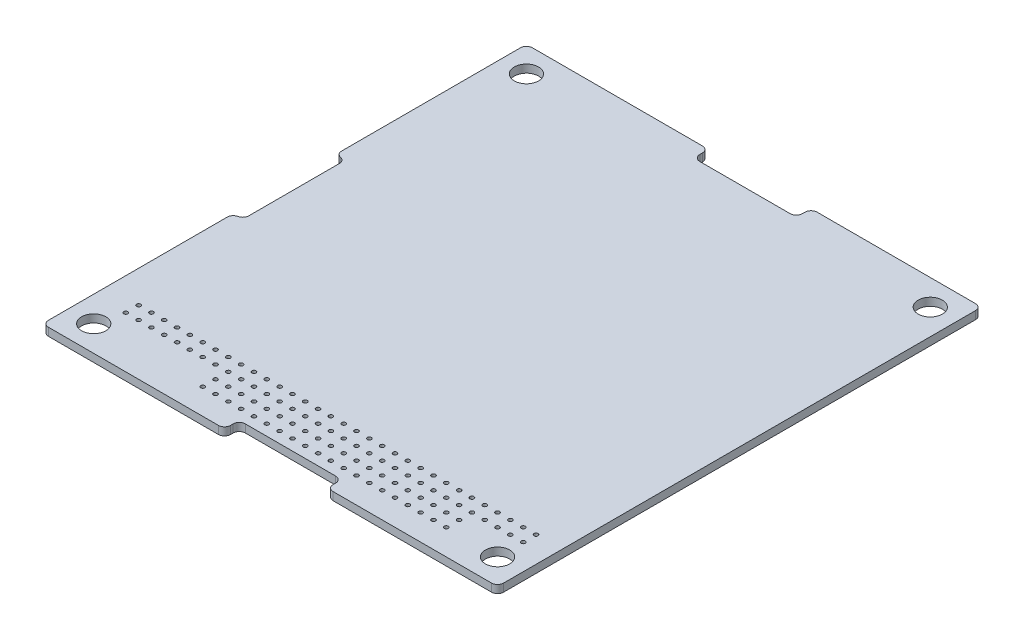
SolidWorks part; units mm, degrees
ref_plane "Front Plane" through (0, 0, 0) normal (0, 0, 1) x (1, 0, 0)
ref_plane "Top Plane" through (0, 0, 0) normal (0, 1, 0) x (1, 0, 0)
ref_plane "Right Plane" through (0, 0, 0) normal (1, 0, 0) x (0, 0, -1)
sketch "Sketch1" plane through (0, 0, 0) normal (0, 1, 0) x (1, 0, 0)
  line L1 (-45.085, -47.945) -> (45.085, -47.945)
  line L2 (-45.085, -47.945) -> (-45.085, 47.945)
  line L3 (-45.085, 47.945) -> (45.085, 47.945)
  line L4 (45.085, -47.945) -> (45.085, 47.945)
  line L5 (-45.085, -47.945) -> (45.085, 47.945) construction
  line L6 (-45.085, 47.945) -> (45.085, -47.945) construction
  point P0 (0, 0)
  dimension "D1" = 95.89
  dimension "D2" = 90.17
extrude "Boss-Extrude1" add sketch "Sketch1" along normal blind 1.57
sketch "Sketch2" plane through (0, 1.57, 0) normal (0, 1, 0) x (1, 0, 0)
  line L0 (-45.085, 47.945) -> (-9.015, 47.945) construction
  line L1 (45.085, 47.945) -> (-45.085, 47.945) construction
  line L2 (-45.085, -47.945) -> (-45.085, -10.135) construction
  line L3 (-9.015, 47.945) -> (11.305, 47.945)
  line L4 (-9.015, 47.945) -> (-9.015, 45.015)
  line L5 (-9.015, 45.015) -> (11.305, 45.015)
  line L6 (11.305, 47.945) -> (11.305, 45.015)
  line L7 (-45.085, 47.945) -> (-45.085, -47.945) construction
  line L8 (-45.085, -47.945) -> (-9.015, -47.945) construction
  line L9 (-45.085, -10.135) -> (-43.165, -10.135)
  line L10 (-45.085, -10.135) -> (-45.085, 10.135)
  line L11 (-45.085, 10.135) -> (-43.165, 10.135)
  line L12 (-43.165, -10.135) -> (-43.165, 10.135)
  line L13 (-45.085, -47.945) -> (45.085, -47.945) construction
  line L15 (-9.015, -47.945) -> (11.305, -47.945)
  line L16 (-9.015, -47.945) -> (-9.015, -45.025)
  line L17 (-9.015, -45.025) -> (11.305, -45.025)
  line L18 (11.305, -47.945) -> (11.305, -45.025)
  dimension "D1" = 36.07
  dimension "D2" = 20.32
  dimension "D3" = 2.93
  dimension "D4" = 37.81
  dimension "D5" = 20.27
  dimension "D6" = 1.92
  dimension "D7" = 2.92
extrude "Cut-Extrude1" cut sketch "Sketch2" against normal blind 1.57
sketch "Sketch3" plane through (0, 1.57, 0) normal (0, 1, 0) x (1, 0, 0)
  line L0 (-45.085, -47.945) -> (-40.005, -47.945) construction
  line L1 (-45.085, -47.945) -> (-9.015, -47.945) construction
  line L2 (-40.005, -47.945) -> (-40.005, -42.865) construction
  line L3 (45.085, -47.945) -> (40.005, -47.945) construction
  line L4 (11.305, -47.945) -> (45.085, -47.945) construction
  line L5 (40.005, -47.945) -> (40.005, -42.865) construction
  line L6 (-45.085, 47.945) -> (-40.005, 47.945) construction
  line L7 (-9.015, 47.945) -> (-45.085, 47.945) construction
  line L8 (-40.005, 47.945) -> (-40.005, 42.865) construction
  circle A0 centre (-40.005, -42.865) radius 2.4
  circle A1 centre (40.005, -42.865) radius 2.4
  circle A2 centre (-40.005, 42.865) radius 2.4
  circle A3 centre (40.005, 42.865) radius 2.4
  dimension "D3" = 4.8
  dimension "D6" = 5.08
  dimension "D4" = 5.08
  dimension "D5" = 4.8
  dimension "D7" = 4.8
  dimension "D8" = 4.8
  dimension "D1" = 5.08
  dimension "D2" = 5.08
extrude "Cut-Extrude2" cut sketch "Sketch3" against normal blind 1.57
fillet "Fillet7" radius 1.2 1 edges at (-9.015, 0.785, 45.025)
fillet "Fillet8" radius 1.2 1 edges at (-9.015, 0.785, 47.945)
fillet "Fillet9" radius 1.2 2 edges at (11.305, 0.785, 47.945) (11.305, 0.785, 45.025)
fillet "Fillet10" radius 1.2 1 edges at (45.085, 0.785, 47.945)
fillet "Fillet11" radius 1.2 1 edges at (45.085, 0.785, -47.945)
fillet "Fillet12" radius 1.2 2 edges at (11.305, 0.785, -45.015) (11.305, 0.785, -47.945)
fillet "Fillet13" radius 1.2 2 edges at (-9.015, 0.785, -47.945) (-9.015, 0.785, -45.015)
fillet "Fillet14" radius 1.2 1 edges at (-45.085, 0.785, -47.945)
fillet "Fillet17" radius 1.2 1 edges at (-45.085, 0.785, -10.135)
fillet "Fillet18" radius 1.2 1 edges at (-43.165, 0.785, -10.135)
fillet "Fillet19" radius 1.2 1 edges at (-45.085, 0.785, 10.135)
fillet "Fillet20" radius 1.2 1 edges at (-43.165, 0.785, 10.135)
fillet "Fillet21" radius 1.2 1 edges at (-45.085, 0.785, 47.945)
sketch "Sketch11" plane through (0, 1.57, 0) normal (0, 1, 0) x (1, 0, 0)
  line L0 (-43.885, -47.945) -> (-45.2926, -47.945) construction
  line L1 (-45.085, -46.745) -> (-45.085, -47.945) construction
  line L2 (-45.085, -47.945) -> (-38.735, -47.945) construction
  line L3 (-43.885, -47.945) -> (-10.215, -47.945) construction
  line L4 (-38.735, -47.945) -> (-38.735, -37.785) construction
  circle A0 centre (-38.735, -37.785) radius 0.4
  circle A1 centre (-36.195, -37.785) radius 0.4
  circle A2 centre (-33.655, -37.785) radius 0.4
  circle A3 centre (-31.115, -37.785) radius 0.4
  circle A4 centre (-28.575, -37.785) radius 0.4
  circle A5 centre (-26.035, -37.785) radius 0.4
  circle A6 centre (-23.495, -37.785) radius 0.4
  circle A7 centre (-20.955, -37.785) radius 0.4
  circle A8 centre (-18.415, -37.785) radius 0.4
  circle A9 centre (-15.875, -37.785) radius 0.4
  circle A10 centre (-13.335, -37.785) radius 0.4
  circle A11 centre (-10.795, -37.785) radius 0.4
  circle A12 centre (-8.255, -37.785) radius 0.4
  circle A13 centre (-5.715, -37.785) radius 0.4
  circle A14 centre (-3.175, -37.785) radius 0.4
  circle A15 centre (-0.635, -37.785) radius 0.4
  circle A16 centre (1.905, -37.785) radius 0.4
  circle A17 centre (4.445, -37.785) radius 0.4
  circle A18 centre (6.985, -37.785) radius 0.4
  circle A19 centre (9.525, -37.785) radius 0.4
  circle A20 centre (12.065, -37.785) radius 0.4
  circle A21 centre (14.605, -37.785) radius 0.4
  circle A22 centre (17.145, -37.785) radius 0.4
  circle A23 centre (19.685, -37.785) radius 0.4
  circle A24 centre (22.225, -37.785) radius 0.4
  circle A25 centre (24.765, -37.785) radius 0.4
  circle A26 centre (27.305, -37.785) radius 0.4
  circle A27 centre (29.845, -37.785) radius 0.4
  circle A28 centre (32.385, -37.785) radius 0.4
  circle A29 centre (34.925, -37.785) radius 0.4
  circle A30 centre (37.465, -37.785) radius 0.4
  circle A31 centre (40.005, -37.785) radius 0.4
  dimension "D3" = 0.8
  dimension "D1" = 6.35
  dimension "D2" = 10.16
  dimension "D4" = 32
extrude "Cut-Extrude8" cut sketch "Sketch11" against normal blind 10
sketch "Sketch12" plane through (0, 1.57, 0) normal (0, 1, 0) x (1, 0, 0)
  line L0 (-38.735, -37.785) -> (-38.735, -35.245) construction
  circle A0 centre (-38.735, -35.245) radius 0.4
  circle A1 centre (-36.195, -35.245) radius 0.4
  circle A2 centre (-33.655, -35.245) radius 0.4
  circle A3 centre (-31.115, -35.245) radius 0.4
  circle A4 centre (-28.575, -35.245) radius 0.4
  circle A5 centre (-26.035, -35.245) radius 0.4
  circle A6 centre (-23.495, -35.245) radius 0.4
  circle A7 centre (-20.955, -35.245) radius 0.4
  circle A8 centre (-18.415, -35.245) radius 0.4
  circle A9 centre (-15.875, -35.245) radius 0.4
  circle A10 centre (-13.335, -35.245) radius 0.4
  circle A11 centre (-10.795, -35.245) radius 0.4
  circle A12 centre (-8.255, -35.245) radius 0.4
  circle A13 centre (-5.715, -35.245) radius 0.4
  circle A14 centre (-3.175, -35.245) radius 0.4
  circle A15 centre (-0.635, -35.245) radius 0.4
  circle A16 centre (1.905, -35.245) radius 0.4
  circle A17 centre (4.445, -35.245) radius 0.4
  circle A18 centre (6.985, -35.245) radius 0.4
  circle A19 centre (9.525, -35.245) radius 0.4
  circle A20 centre (12.065, -35.245) radius 0.4
  circle A21 centre (14.605, -35.245) radius 0.4
  circle A22 centre (17.145, -35.245) radius 0.4
  circle A23 centre (19.685, -35.245) radius 0.4
  circle A24 centre (22.225, -35.245) radius 0.4
  circle A25 centre (24.765, -35.245) radius 0.4
  circle A26 centre (27.305, -35.245) radius 0.4
  circle A27 centre (29.845, -35.245) radius 0.4
  circle A28 centre (32.385, -35.245) radius 0.4
  circle A29 centre (34.925, -35.245) radius 0.4
  circle A30 centre (37.465, -35.245) radius 0.4
  circle A31 centre (40.005, -35.245) radius 0.4
  dimension "D2" = 0.8
  dimension "D1" = 2.54
  dimension "D3" = 32
extrude "Cut-Extrude9" cut sketch "Sketch12" against normal blind 10
sketch "Sketch13" plane through (0, 1.57, 0) normal (0, 1, 0) x (1, 0, 0)
  line L0 (-43.885, -47.945) -> (-45.085, -47.945) construction
  line L1 (-45.085, -47.945) -> (-45.085, -46.745) construction
  line L2 (-45.085, -47.945) -> (-18.415, -47.945) construction
  line L3 (-43.885, -47.945) -> (-10.215, -47.945) construction
  line L4 (-18.415, -47.945) -> (-18.415, -42.865) construction
  circle A0 centre (-18.415, -42.865) radius 0.4
  circle A1 centre (-15.875, -42.865) radius 0.4
  circle A2 centre (-13.335, -42.865) radius 0.4
  circle A3 centre (-10.795, -42.865) radius 0.4
  circle A4 centre (-8.255, -42.865) radius 0.4
  circle A5 centre (-5.715, -42.865) radius 0.4
  circle A6 centre (-3.175, -42.865) radius 0.4
  circle A7 centre (-0.635, -42.865) radius 0.4
  circle A8 centre (1.905, -42.865) radius 0.4
  circle A9 centre (4.445, -42.865) radius 0.4
  circle A10 centre (6.985, -42.865) radius 0.4
  circle A11 centre (9.525, -42.865) radius 0.4
  circle A12 centre (12.065, -42.865) radius 0.4
  circle A13 centre (14.605, -42.865) radius 0.4
  circle A14 centre (17.145, -42.865) radius 0.4
  circle A15 centre (19.685, -42.865) radius 0.4
  circle A16 centre (22.225, -42.865) radius 0.4
  circle A17 centre (24.765, -42.865) radius 0.4
  circle A18 centre (27.305, -42.865) radius 0.4
  circle A19 centre (29.845, -42.865) radius 0.4
  dimension "D3" = 0.8
  dimension "D1" = 26.67
  dimension "D2" = 5.08
  dimension "D4" = 20
extrude "Cut-Extrude10" cut sketch "Sketch13" against normal blind 10
sketch "Sketch14" plane through (0, 1.57, 0) normal (0, 1, 0) x (1, 0, 0)
  line L0 (-18.415, -42.865) -> (-18.415, -40.325) construction
  circle A0 centre (-18.415, -40.325) radius 0.4
  circle A1 centre (-15.875, -40.325) radius 0.4
  circle A2 centre (-13.335, -40.325) radius 0.4
  circle A3 centre (-10.795, -40.325) radius 0.4
  circle A4 centre (-8.255, -40.325) radius 0.4
  circle A5 centre (-5.715, -40.325) radius 0.4
  circle A6 centre (-3.175, -40.325) radius 0.4
  circle A7 centre (-0.635, -40.325) radius 0.4
  circle A8 centre (1.905, -40.325) radius 0.4
  circle A9 centre (4.445, -40.325) radius 0.4
  circle A10 centre (6.985, -40.325) radius 0.4
  circle A11 centre (9.525, -40.325) radius 0.4
  circle A12 centre (12.065, -40.325) radius 0.4
  circle A13 centre (14.605, -40.325) radius 0.4
  circle A14 centre (17.145, -40.325) radius 0.4
  circle A15 centre (19.685, -40.325) radius 0.4
  circle A16 centre (22.225, -40.325) radius 0.4
  circle A17 centre (24.765, -40.325) radius 0.4
  circle A18 centre (27.305, -40.325) radius 0.4
  circle A19 centre (29.845, -40.325) radius 0.4
  dimension "D2" = 0.8
  dimension "D1" = 2.54
  dimension "D3" = 20
extrude "Cut-Extrude11" cut sketch "Sketch14" against normal blind 10
